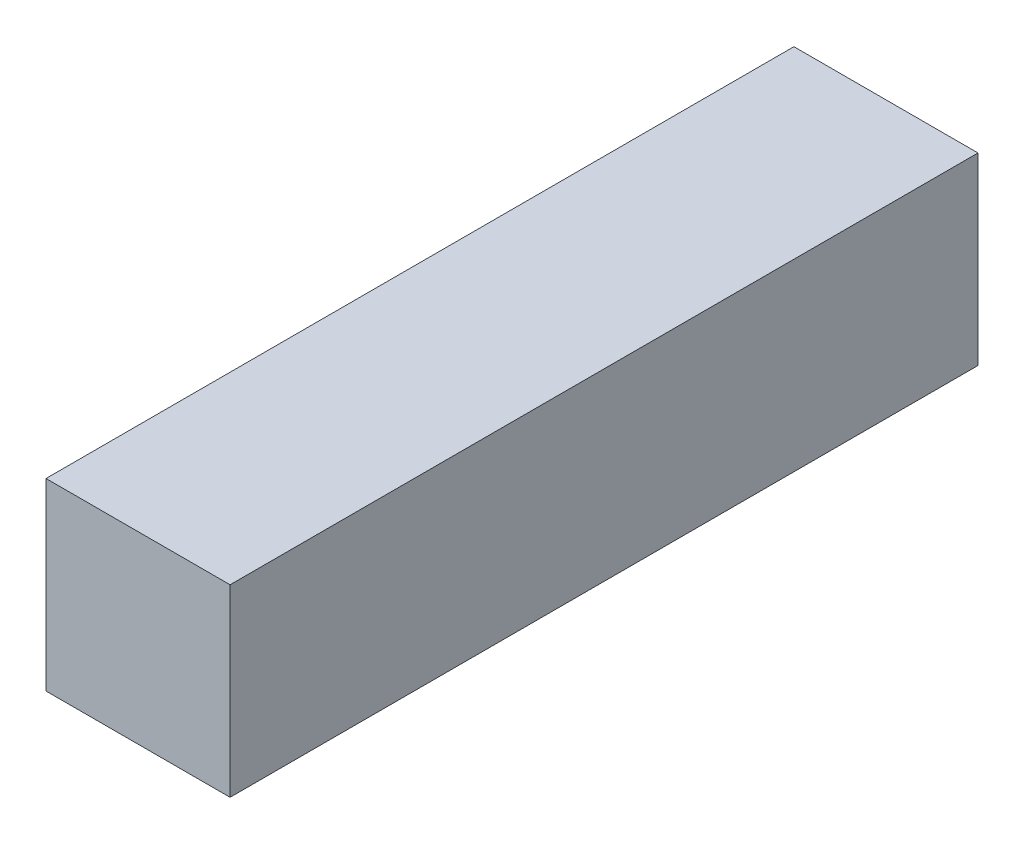
SolidWorks part; units mm, degrees
ref_plane "Front Plane" through (0, 0, 0) normal (0, 0, 1) x (1, 0, 0)
ref_plane "Top Plane" through (0, 0, 0) normal (0, 1, 0) x (1, 0, 0)
ref_plane "Right Plane" through (0, 0, 0) normal (1, 0, 0) x (0, 0, -1)
sketch "Sketch1" plane through (0, 0, 0) normal (0, 0, 1) x (1, 0, 0)
  line L1 (-2.46, -2.46) -> (2.46, -2.46)
  line L2 (-2.46, -2.46) -> (-2.46, 2.46)
  line L3 (-2.46, 2.46) -> (2.46, 2.46)
  line L4 (2.46, -2.46) -> (2.46, 2.46)
  line L5 (-2.46, -2.46) -> (2.46, 2.46) construction
  line L6 (-2.46, 2.46) -> (2.46, -2.46) construction
  point P0 (0, 0)
  dimension "D1" = 4.92
  dimension "D2" = 4.92
extrude "Boss-Extrude1" add sketch "Sketch1" along normal blind 19.99
